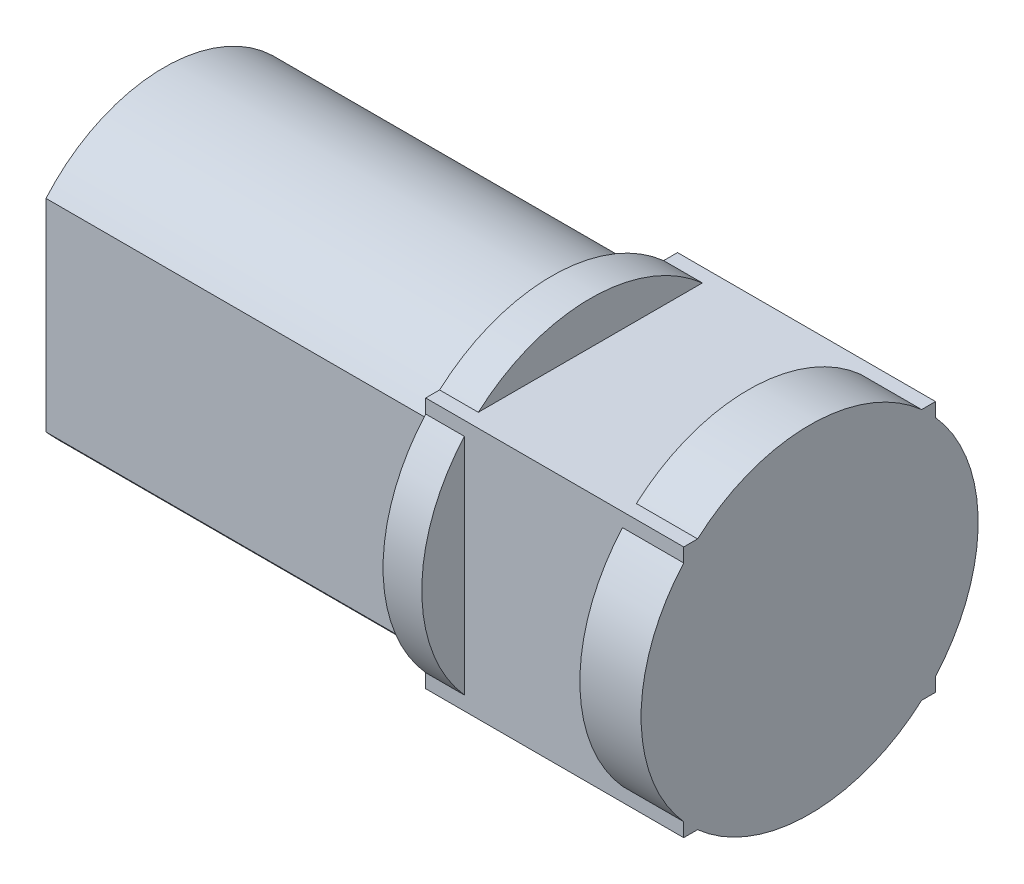
SolidWorks part; units mm, degrees
ref_plane "Front Plane" through (0, 0, 0) normal (0, 0, 1) x (1, 0, 0)
ref_plane "Top Plane" through (0, 0, 0) normal (0, 1, 0) x (1, 0, 0)
ref_plane "Right Plane" through (0, 0, 0) normal (1, 0, 0) x (0, 0, -1)
other "Bounding Box"
ref_plane "Default Plane" through (-8.9266, -12.7485, 0) normal (-0.1736, 0.9848, 0) x (0.9848, 0.1736, 0)
sketch "Sketch1" plane through (0, 0, 0) normal (1, 0, 0) x (0, 0, -1)
  line L1 (-8.255, 8.255) -> (8.255, 8.255)
  line L2 (-8.255, 8.255) -> (-8.255, -8.255)
  line L3 (-8.255, -8.255) -> (8.255, -8.255)
  line L4 (8.255, 8.255) -> (8.255, -8.255)
  line L5 (-8.255, 8.255) -> (8.255, -8.255) construction
  line L6 (-8.255, -8.255) -> (8.255, 8.255) construction
  point P0 (0, 0)
  dimension "D1" = 16.51
extrude "Boss-Extrude1" add sketch "Sketch1" along normal mid plane 16.9164
sketch "Sketch2" plane through (8.4582, 0, 0) normal (1, 0, 0) x (0, 0, -1)
  circle A0 centre (0, 0) radius 11.049
  dimension "D1" = 22.098
extrude "Boss-Extrude2" add sketch "Sketch2" against normal blind 4.0132
sketch "Sketch3" plane through (-8.4582, 0, 0) normal (-1, 0, 0) x (0, 0, 1)
  circle A0 centre (0, 0) radius 11.049
  arc A1 (8.255, -7.3441) -> (8.255, 7.3441) centre (0, 0) ccw construction
extrude "Boss-Extrude3" add sketch "Sketch3" against normal blind 2.54
sketch "Sketch4" plane through (-8.4582, 0, 0) normal (-1, 0, 0) x (0, 0, 1)
  line L0 (-7.747, -6.6321) -> (-7.747, 6.6321)
  line L1 (7.747, -6.6321) -> (7.747, 6.6321)
  arc A0 (-7.747, -6.6321) -> (7.747, -6.6321) centre (0, 0) ccw
  arc A1 (7.747, 6.6321) -> (-7.747, 6.6321) centre (0, 0) ccw
  dimension "D1" = 20.3962
  dimension "D2" = 15.494
extrude "Boss-Extrude4" add sketch "Sketch4" along normal blind 25.4
